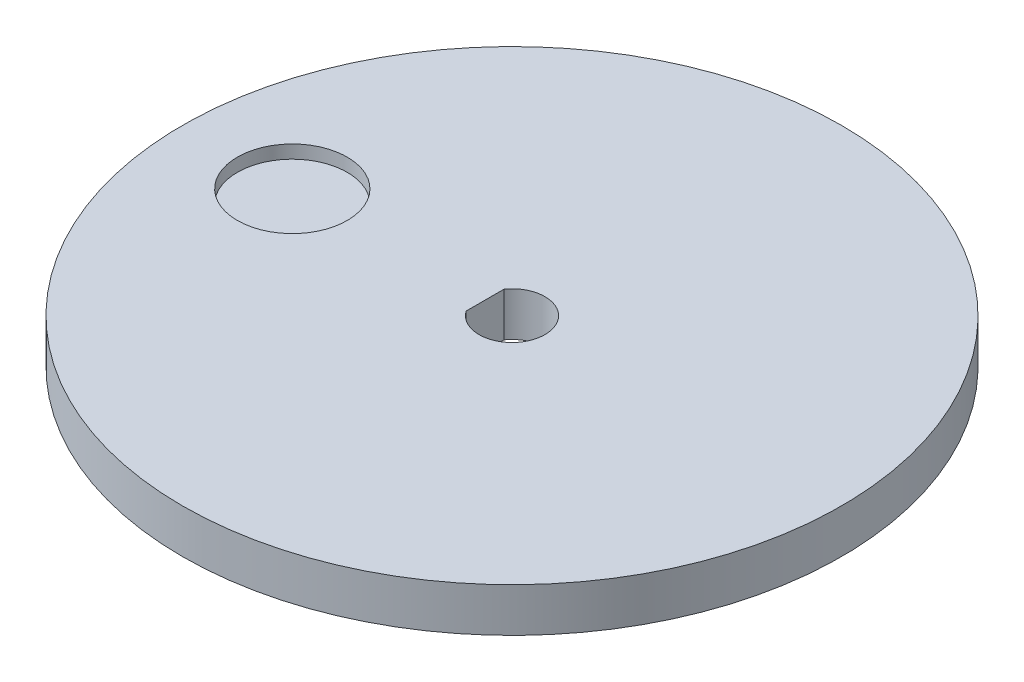
SolidWorks part; units mm, degrees
ref_plane "Front Plane" through (0, 0, 0) normal (0, 0, 1) x (1, 0, 0)
ref_plane "Top Plane" through (0, 0, 0) normal (0, 1, 0) x (1, 0, 0)
ref_plane "Right Plane" through (0, 0, 0) normal (1, 0, 0) x (0, 0, -1)
sketch "Sketch1" plane through (0, 0, 0) normal (0, 1, 0) x (1, 0, 0)
  line L1 (-2.45, 1.7313) -> (-2.45, 0)
  line L2 (-2.45, 0) -> (-2.45, -1.7313)
  circle A0 centre (0, 0) radius 30
  arc A1 (-2.45, -1.7313) -> (-2.45, 1.7313) centre (0, 0) ccw
extrude "Boss-Extrude1" add sketch "Sketch1" along normal blind 4
sketch "Sketch2" plane through (0, 4, 0) normal (0, 1, 0) x (1, 0, 0)
  circle A0 centre (-20, 0) radius 5
  dimension "D1" = 20
extrude "Cut-Extrude1" cut sketch "Sketch2" against normal blind 1.2
